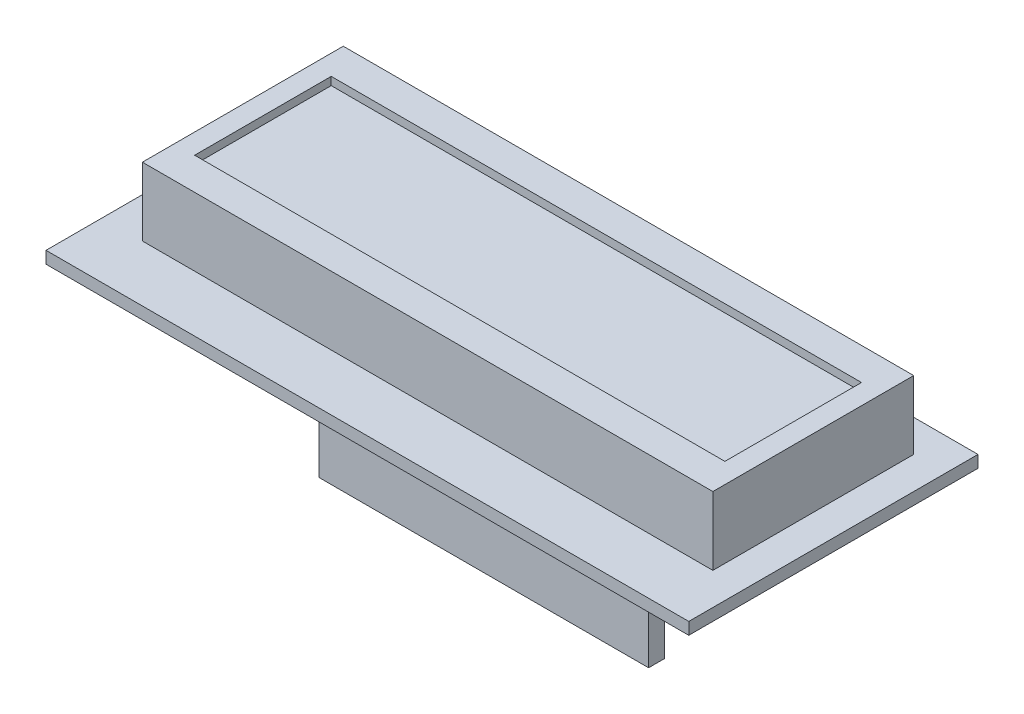
SolidWorks part; units mm, degrees
ref_plane "Plan de face" through (0, 0, 0) normal (0, 0, 1) x (1, 0, 0)
ref_plane "Plan de dessus" through (0, 0, 0) normal (0, 1, 0) x (1, 0, 0)
ref_plane "Plan de droite" through (0, 0, 0) normal (1, 0, 0) x (0, 0, -1)
sketch "Esquisse1" plane through (0, 0, 0) normal (0, 1, 0) x (1, 0, 0)
  line L1 (4, -1.8) -> (-4, -1.8)
  line L2 (4, -1.8) -> (4, 1.8)
  line L3 (4, 1.8) -> (-4, 1.8)
  line L4 (-4, -1.8) -> (-4, 1.8)
  line L5 (4, -1.8) -> (-4, 1.8) construction
  line L6 (4, 1.8) -> (-4, -1.8) construction
  point P0 (0, 0)
  dimension "D1" = 8
  dimension "D2" = 3.6
extrude "Boss.-Extru.1" add sketch "Esquisse1" along normal blind 0.15
sketch "Esquisse2" plane through (0, 0.15, 0) normal (0, 1, 0) x (1, 0, 0)
  line L0 (-4, -1.8) -> (4, -1.8) construction
  line L1 (-3.5, 1.4) -> (3.6, 1.4)
  line L2 (-3.5, 1.4) -> (-3.5, -1.1)
  line L3 (-3.5, -1.1) -> (3.6, -1.1)
  line L4 (3.6, 1.4) -> (3.6, -1.1)
  line L5 (4, -1.8) -> (4, 1.8) construction
  dimension "D1" = 7.1
  dimension "D2" = 2.5
  dimension "D3" = 0.7
  dimension "D4" = 0.4
extrude "Boss.-Extru.2" add sketch "Esquisse2" along normal blind 0.85 contours L1 L4 L3 L2
sketch "Esquisse3" plane through (0, 0, 0) normal (0, -1, 0) x (1, 0, 0)
  line L0 (-4, 1.8) -> (4, 1.8) construction
  line L1 (-0.7, 1.7) -> (3.4, 1.7)
  line L2 (-0.7, 1.7) -> (-0.7, 1.5)
  line L3 (-0.7, 1.5) -> (3.4, 1.5)
  line L4 (3.4, 1.7) -> (3.4, 1.5)
  line L5 (4, 1.8) -> (4, -1.8) construction
  dimension "D1" = 0.1
  dimension "D2" = 0.6
  dimension "D3" = 4.1
  dimension "D4" = 0.2
extrude "Boss.-Extru.3" add sketch "Esquisse3" along normal blind 0.7
sketch "Esquisse4" plane through (0, 1, 0) normal (0, 1, 0) x (1, 0, 0)
  line L0 (-3.25, 1) -> (-3.25, -0.7)
  line L1 (-3.25, 1) -> (3.35, 1)
  line L2 (-3.25, -0.7) -> (3.35, -0.7)
  line L3 (3.35, 1) -> (3.35, -0.7)
  line L4 (-3.5, 1.4) -> (3.6, 1.4) construction
  line L5 (-3.5, -1.1) -> (3.6, -1.1) construction
  line L6 (-3.5, 1.4) -> (-3.5, -1.1) construction
  line L7 (3.6, 1.4) -> (3.6, -1.1) construction
  dimension "D1" = 0.4
  dimension "D2" = 0.4
  dimension "D3" = 0.25
  dimension "D4" = 0.25
extrude "Enlèv. mat.-Extru.1" cut sketch "Esquisse4" against normal blind 0.1 contours L1 L3 L2 L0
